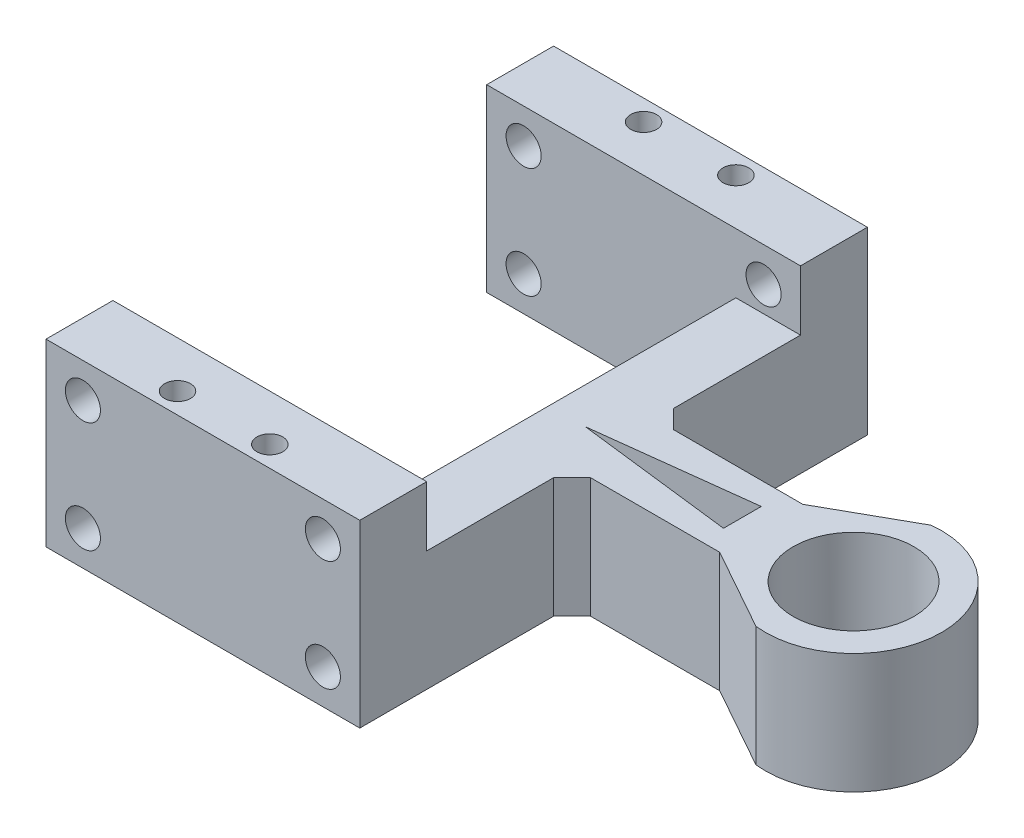
SolidWorks part; units mm, degrees
ref_plane "Front Plane" through (0, 0, 0) normal (0, 0, 1) x (1, 0, 0)
ref_plane "Top Plane" through (0, 0, 0) normal (0, 1, 0) x (1, 0, 0)
ref_plane "Right Plane" through (0, 0, 0) normal (1, 0, 0) x (0, 0, -1)
sketch "Sketch8" plane through (0, 0, 0) normal (0, 1, 0) x (1, 0, 0)
  line L2 (0, 0) -> (65.8381, 0) construction
  line L4 (0, 0) -> (50, 0) construction
  line L5 (34, 4.5) -> (50, 4.5)
  line L6 (50, 4.5) -> (58.908, 9.4874)
  line L7 (34, -4.5) -> (50, -4.5)
  line L8 (50, -4.5) -> (58.908, -9.4874)
  line L9 (34, 4.5) -> (34, 27.5)
  line L12 (34, 27.5) -> (0, 27.5)
  line L13 (0, 27.5) -> (0, 20.25)
  line L14 (0, -20.25) -> (0, -27.5)
  line L15 (0, -27.5) -> (34, -27.5)
  line L16 (34, -27.5) -> (34, -4.5)
  line L17 (27, 4.5) -> (27, -4.5)
  line L18 (0, 20.25) -> (27, 20.25)
  line L20 (0, -20.25) -> (27, -20.25)
  line L21 (27, 20.25) -> (27, -20.25)
  line L22 (0, 25.25) -> (34, 25.25) construction
  circle A0 centre (60, 0) radius 4.5
  arc A1 (58.908, -9.4874) -> (58.908, 9.4874) centre (60, 0) ccw
  circle A2 centre (60, 0) radius 6.55 construction
  circle A5 centre (22, 25.25) radius 1.4
  circle A6 centre (12, 25.25) radius 1.4
  circle A7 centre (22, -25.25) radius 1.4
  circle A8 centre (12, -25.25) radius 1.4
  point P2 (27, 0)
  point P3 (27, 0)
  dimension "D1" = 9
  dimension "D4" = 3
  dimension "D6" = 13.1
  dimension "D13" = 2.8
  dimension "D2" = 40.5
  dimension "D3" = 10
  dimension "D5" = 9
  dimension "D7" = 26
  dimension "D8" = 5
  dimension "D9" = 55
  dimension "D10" = 7
  dimension "D11" = 27
  dimension "D14" = 5
  dimension "D15" = 10
extrude "Boss-Extrude2" add sketch "Sketch8" along normal blind 19.5
sketch "Sketch10" plane through (0, 19.5, 0) normal (0, 1, 0) x (1, 0, 0)
  circle A0 centre (60, 0) radius 6.55
  dimension "D1" = 13.1
extrude "Cut-Extrude6" cut sketch "Sketch10" against normal offset from surface (16.5 mm away) 3 up to face at (22, 0, 26.65)
sketch "Sketch12" plane through (0, 0, 0) normal (0, 0, 1) x (1, 0, 0)
  line L0 (30, 15.75) -> (30, 3.75) construction
  line L3 (0, 9.75) -> (71.8198, 9.75) construction
  line L4 (0, 19.5) -> (0, 0) construction
  line L5 (4, 15.75) -> (4, 3.75) construction
  line L7 (34, 19.5) -> (34, 0) construction
  circle A0 centre (4, 15.75) radius 1.9
  circle A1 centre (4, 3.75) radius 1.9
  circle A2 centre (30, 15.75) radius 1.9
  circle A3 centre (30, 3.75) radius 1.9
  point P0 (4, 9.75)
  point P8 (30, 9.75)
  dimension "D2" = 3.8
  dimension "D1" = 4
  dimension "D3" = 12
  dimension "D4" = 4
extrude "Cut-Extrude7" cut sketch "Sketch12" against normal blind 47 and the other way blind 43
sketch "Sketch13" plane through (0, 0, 0) normal (0, 0, 1) x (1, 0, 0)
  line L0 (0, 19.5) -> (34, 19.5) construction
  line L8 (23.2142, 19.5) -> (23.2142, 13)
  line L10 (69.55, 0) -> (69.55, 19.5) construction
  line L11 (69.55, 13) -> (69.55, 19.5)
  line L12 (69.55, 19.5) -> (23.2142, 19.5)
  line L14 (23.2142, 13) -> (69.55, 13)
  dimension "D1" = 13
extrude "Cut-Extrude8" cut sketch "Sketch13" against normal up to surface and the other way up to surface up to face at (2.1, 15.75, -20.25) other way up to face at (2.1, 15.75, 20.25)
sketch "Sketch14" plane through (0, 0, 0) normal (0, 1, 0) x (1, 0, 0)
  line L0 (34, 9.789) -> (50, 4.5)
  line L2 (50, 4.5) -> (34, 4.5)
  line L3 (34, 4.5) -> (34, 9.789)
  line L4 (0, 0) -> (75.8263, 0) construction
  line L8 (34, -27.5) -> (34, -20.25) construction
  line L9 (34, -4.5) -> (34, -9.789)
  line L10 (50, -4.5) -> (34, -4.5)
  line L11 (34, -9.789) -> (50, -4.5)
extrude "Boss-Extrude3" [suppressed] add sketch "Sketch14" along normal blind 3
chamfer "Chamfer2" distance 2 angle 45 2 edges at (34, 6.5, 4.5) (34, 6.5, -4.5)
sketch "Sketch16" plane through (0, 0, 0) normal (0, 1, 0) x (1, 0, 0)
  line L0 (0, 0) -> (95.9074, 0) construction
  line L4 (47.9537, -2.0479) -> (47.9537, 2.0479)
  line L5 (47.9537, 2.0479) -> (30.9346, 0)
  line L6 (30.9346, 0) -> (47.9537, -2.0479)
  point P6 (47.9537, 0)
extrude "Cut-Extrude9" cut sketch "Sketch16" along normal up to surface (13 mm away) up to face at (60, 13, -6.55)
